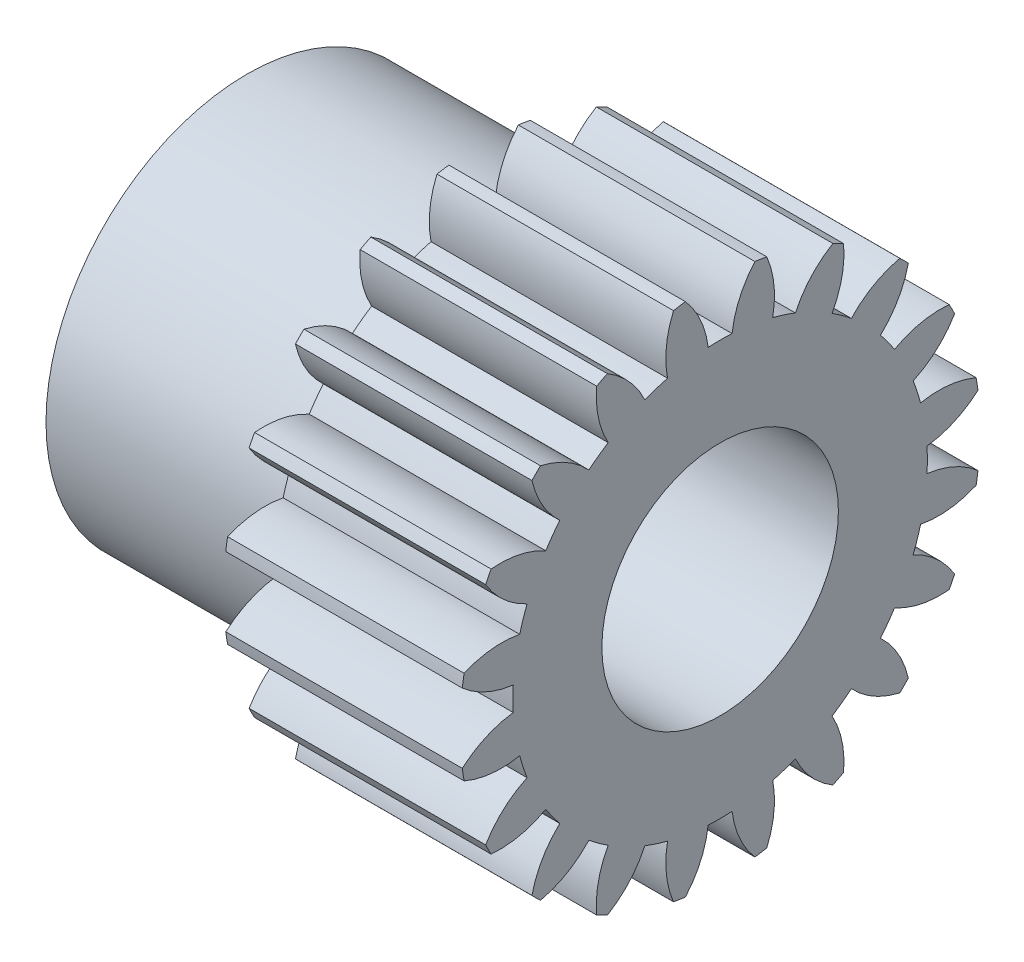
SolidWorks part; units mm, degrees
material "Plain Carbon Steel"
ref_plane "Plane1" through (0, 0, 0) normal (0, 0, 1) x (1, 0, 0)
ref_plane "Plane2" through (0, 0, 0) normal (0, 1, 0) x (1, 0, 0)
ref_plane "Plane3" through (0, 0, 0) normal (1, 0, 0) x (0, 0, -1)
sketch "HoldingSke" plane through (0, 0, 0) normal (0, 1, 0) x (1, 0, 0)
  line L0 (0, 0) -> (477.3639, -173.7462)
  line L1 (-15, 0) -> (100, 0) construction
  line L2 (0, 0) -> (-2.1039, 2.3779)
  line L3 (0, 0) -> (-11.863, 4.5341)
  line L4 (0, 0) -> (8.1152, 2.9537)
  line L5 (0, 0) -> (-23.7986, -8.8762)
  line L6 (0, 0) -> (-10.5278, -7.1032)
  line L7 (-2.1039, 2.3779) -> (3.3635, 27.1825)
  line L8 (-76.2, 54.61) -> (-61.976, 54.61)
  line L9 (-71.009, 38.7566) -> (-53.1078, 45.2721)
  line L10 (-76.2, 71.12) -> (104.1128, 71.12)
  line L11 (0, 0) -> (-12.7, 0)
  line L12 (-76.2, 101.6) -> (-76.1492, 101.6)
  line L13 (24.9733, 27.94) -> (52.9518, 28.4284)
  line L14 (24.9733, 27.94) -> (25.0241, 27.9398)
  line L15 (24.9733, 27.94) -> (100.4021, 29.52)
  circle A0 centre (0, 0) radius 6.35
  circle A1 centre (0, 0) radius 10.795
  circle A2 centre (0, 0) radius 10.795
  circle A3 centre (0, 0) radius 6.35
  dimension "MHD" = 21.59
  dimension "Hub_dia" = 21.59
  dimension "Bore" = 12.7
  dimension "MBD" = 12.7
  dimension "Num_teeth" = 20
  dimension "Pitch_radius" = 180.3128
  dimension "Pitch" = 508
  dimension "Width" = 12.7
  dimension "Overall_len" = 25.4
  dimension "Show_teeth" = 20
  dimension "Thickness" = 12.7
  dimension "OAL" = 25.4001
  dimension "T_dim" = 14.224
  dimension "Ap" = 20
  dimension "H" = 19.05
  dimension "Backlash" = 0.0508
  dimension "Addendum_fac" = 1
  dimension "Dedendum_fac" = 1.2
  dimension "Clearance_fac" = 0.2
  dimension "Dedendum_add" = 0.0508
sketch "BasProSke" plane through (0, 0, 0) normal (0, 1, 0) x (1, 0, 0)
  line L0 (-10, 0) -> (60, 0) construction
  line L1 (0, 0) -> (0, 13.97)
  line L2 (0, 0) -> (12.7, 0)
  line L3 (12.7, 0) -> (12.7, 13.97)
  line L4 (12.7, 13.97) -> (0, 13.97)
  dimension "Diameter" = 27.94
  dimension "Thickness" = 12.7
revolve "Base-Revolve" add sketch "BasProSke" angle 360 about L0
sketch "TooCutSke" plane through (0, 0, 0) normal (1, 0, 0) x (0, 0, -1)
  line L1 (0, 0) -> (0, 107) construction
  line L2 (0, 0) -> (-1.0853, 12.6535) construction
  line L3 (0, 0) -> (-3.9633, 25.0231) construction
  line L4 (-1.0853, 12.6535) -> (-1.9816, 12.5116) construction
  arc A0 (0.6405, 11.1067) -> (-0.6405, 11.1067) centre (0, 0) ccw
  arc A1 (1.8856, 13.8678) -> (-1.8856, 13.8678) centre (0, 0) ccw
  circle A2 centre (0, 0) radius 12.7 construction
  circle A3 centre (0, 0) radius 11.9341 construction
  arc A4 (-0.6405, 11.1067) -> (-1.8856, 13.8678) centre (-5.6834, 10.4939) ccw
  arc A5 (1.8856, 13.8678) -> (0.6405, 11.1067) centre (5.6834, 10.4939) ccw
  dimension "Root_dia" = 22.2504
  dimension "Overcut_dia" = 27.9908
  dimension "Pitch_dia" = 25.4
  dimension "Base_dia" = 23.8682
  dimension "Flank_rad" = 5.08
  dimension "Half_ang" = 9
  dimension "Half_CT" = 0.9075
extrude "ToothCut" cut sketch "TooCutSke" along normal through all
fillet "Breaks" [suppressed] radius 0.0254
fillet "RootFillets" [suppressed] radius 0.3048
pattern_circular "TeethCuts" count 20 every 18 about axis through (-10, 0, 0) along (1, 0, 0) of "ToothCut", "RootFillets", "Breaks"
sketch "HubNeaOneSke" plane through (0, 0, 0) normal (-1, 0, 0) x (0, 0, 1)
  circle A0 centre (0, 0) radius 10.795
  dimension "Diameter" = 21.59
extrude "HubNearOne" add sketch "HubNeaOneSke" along normal blind 12.7001
sketch "HubNeaBotSke" plane through (0, 0, 0) normal (-1, 0, 0) x (0, 0, 1)
  circle A0 centre (0, 0) radius 10.795
  dimension "Diameter" = 21.59
extrude "HubNearBoth" [suppressed] add sketch "HubNeaBotSke" along normal blind 6.35
ref_plane "FarPln" through (12.7, 0, 0) normal (1, 0, 0) x (0, 0, -1)
sketch "HubFarSke" plane through (12.7, 0, 0) normal (1, 0, 0) x (0, 0, -1)
  circle A0 centre (0, 0) radius 10.795
  dimension "Diameter" = 21.59
extrude "HubFar" [suppressed] add sketch "HubFarSke" along normal blind 6.35
sketch "BorSke" plane through (0, 0, 0) normal (1, 0, 0) x (0, 0, -1)
  circle A0 centre (0, 0) radius 6.35
  dimension "Diameter" = 12.7
extrude "Bore" cut sketch "BorSke" along normal mid plane 50.8001
sketch "KeySke" plane through (0, 0, 0) normal (1, 0, 0) x (0, 0, -1)
  line L0 (-1.5875, 0) -> (-1.5875, 7.874)
  line L1 (-1.5875, 7.874) -> (1.5875, 7.874)
  line L2 (1.5875, 7.874) -> (1.5875, 0)
  line L3 (0, 0) -> (0, 34) construction
  line L4 (-1.5875, 0) -> (1.5875, 0)
  dimension "Offset" = 7.874
  dimension "Width" = 3.175
extrude "Keyway" [suppressed] cut sketch "KeySke" along normal mid plane 50.8001
pattern_circular "Keyway2" [suppressed] count 2 every 90 about axis through (-10, 0, 0) along (1, 0, 0)
equation "' \"Pitch@HoldingSke\" = 4"
equation "' \"Num_teeth@HoldingSke\" = 12"
equation "' \"Ap@HoldingSke\" =  20"
equation "' \"Width@HoldingSke\" = 0.5"
equation "' \"Hub_dia@HoldingSke\"= 1"
equation "' \"Overall_len@HoldingSke\" = 1.0"
equation "' \"Bore@HoldingSke\" = 0.75"
equation "' \"T_dim@HoldingSke\" = 0.85"
equation "' \"Width@KeySke\" = 0.25"
equation "' \"Show_teeth@HoldingSke\" = 13"
equation "' \"Backlash@HoldingSke\" = 0.009"
equation "' \"Addendum_fac@HoldingSke\" = 1.0"
equation "' \"Dedendum_fac@HoldingSke\" = 1.25"
equation "' \"Dedendum_add@HoldingSke\" = 0.00005"
equation "' \"Clearance_fac@HoldingSke\" = 0.25"
equation "' \"Pitch@HoldingSke\" = 0.5"
equation "' \"Num_teeth@HoldingSke\" = 23"
equation "' \"Show_teeth@HoldingSke\" = 23"
equation "' \"Backlash@HoldingSke\" = 0.0375"
equation "\"Overcut_dia@TooCutSke\" = (\"Num_teeth@HoldingSke\" + 2 * \"Addendum_fac@HoldingSke\") / \"Pitch@HoldingSke\" + 0.002"
equation "\"Pitch_dia@TooCutSke\" = \"Num_teeth@HoldingSke\" / \"Pitch@HoldingSke\""
equation "\"Base_dia@TooCutSke\" = \"Num_teeth@HoldingSke\" / \"Pitch@HoldingSke\" * cos((\"Ap@HoldingSke\"  * 3.14159265 / 180))"
equation "\"Root_dia@TooCutSke\" = (\"Num_teeth@HoldingSke\" + 2) / \"Pitch@HoldingSke\" - 2 * (\"Addendum_fac@HoldingSke\" + \"Dedendum_fac@HoldingSke\") / \"Pitch@HoldingSke\" - \"Dedendum_add@HoldingSke\" * 2"
equation "\"Half_ang@TooCutSke\" = 180 / \"Num_teeth@HoldingSke\""
equation "\"Half_CT@TooCutSke\" = \"Num_teeth@HoldingSke\" / \"Pitch@HoldingSke\" * sin((3.14159265 / 2 / \"Num_teeth@HoldingSke\")) / 2 - 7 * \"Backlash@HoldingSke\" / 4"
equation "\"Flank_rad@TooCutSke\" = \"Num_teeth@HoldingSke\" / \"Pitch@HoldingSke\" / 5"
equation "\"Radius@RootFillets\" = \"Clearance_fac@HoldingSke\" / \"Pitch@HoldingSke\" + \"Dedendum_add@HoldingSke\""
equation "\"Break_rad@Breaks\" = 0.02 / \"Pitch@HoldingSke\""
equation "\"Thickness@HoldingSke\" = \"Width@HoldingSke\""
equation "\"OAL@HoldingSke\" = \"Thickness@HoldingSke\""
equation "\"MHD@HoldingSke\" = (\"Num_teeth@HoldingSke\" + 2) / \"Pitch@HoldingSke\" - 2 * (\"Addendum_fac@HoldingSke\" + \"Dedendum_fac@HoldingSke\")  / \"Pitch@HoldingSke\" - \"Dedendum_add@HoldingSke\" * 2"
equation "\"MBD@HoldingSke\" = (\"Num_teeth@HoldingSke\" + 2) / \"Pitch@HoldingSke\" - 2 * (\"Addendum_fac@HoldingSke\" + \"Dedendum_fac@HoldingSke\")  / \"Pitch@HoldingSke\" - \"Dedendum_add@HoldingSke\" * 2 - 0.002"
equation "\"MHD@HoldingSke\" = ((sgn( \"MHD@HoldingSke\" - \"Hub_dia@HoldingSke\" )-1)*( \"MHD@HoldingSke\" - \"Hub_dia@HoldingSke\" ))/-2+ \"Hub_dia@HoldingSke\""
equation "\"MBD@HoldingSke\" = ((sgn( \"MBD@HoldingSke\" - \"Bore@HoldingSke\" )-1)*( \"MBD@HoldingSke\" - \"Bore@HoldingSke\" ))/-2+ \"Bore@HoldingSke\""
equation "\"OAL@HoldingSke\" = ((sgn( \"OAL@HoldingSke\" - \"Overall_len@HoldingSke\" )+1)*( \"OAL@HoldingSke\" - \"Overall_len@HoldingSke\" ))/2 + \"Overall_len@HoldingSke\" + 0.000002"
equation "\"Num_teeth@TeethCuts\" = int( \"Show_teeth@HoldingSke\" ) + 1"
equation "\"Num_teeth@TeethCuts\" = ((sgn( \"Num_teeth@TeethCuts\" - \"Num_teeth@HoldingSke\" )-1)*( \"Num_teeth@TeethCuts\" - \"Num_teeth@HoldingSke\" ))/-2+ \"Num_teeth@HoldingSke\""
equation "\"Num_teeth@TeethCuts\" = ((sgn( \"Num_teeth@TeethCuts\" - 2.0)+1)*( \"Num_teeth@TeethCuts\" - 2.0))/2 +2.0"
equation "\"Angle@TeethCuts\" = 360.0 / \"Num_teeth@HoldingSke\""
equation "\"Diameter@BasProSke\" = (\"Num_teeth@HoldingSke\" + 2 * \"Addendum_fac@HoldingSke\") / \"Pitch@HoldingSke\""
equation "\"Thickness@BasProSke\"  = \"Thickness@HoldingSke\""
equation "' \"Fillet_rad@BasProSke\" =  \"Thickness@HoldingSke\" * 0.05"
equation "\"MHD@HoldingSke\" = ((sgn( \"MHD@HoldingSke\" - \"Root_dia@TooCutSke\" )-1)*( \"MHD@HoldingSke\" - \"Root_dia@TooCutSke\" ))/-2+ \"Root_dia@TooCutSke\""
equation "\"Diameter@HubNeaOneSke\" = \"MHD@HoldingSke\""
equation "\"Length@HubNearOne\" = \"OAL@HoldingSke\" - \"Thickness@BasProSke\""
equation "\"Diameter@HubNeaBotSke\" = \"MHD@HoldingSke\""
equation "\"Length@HubNearBoth\" = ( \"OAL@HoldingSke\" - \"Thickness@BasProSke\" ) / 2.0"
equation "\"Thickness@FarPln\" = \"Thickness@BasProSke\""
equation "\"Diameter@HubFarSke\" = \"MHD@HoldingSke\""
equation "\"Length@HubFar\" = ( \"OAL@HoldingSke\" - \"Thickness@BasProSke\" ) / 2.0"
equation "\"Diameter@BorSke\" = \"MBD@HoldingSke\""
equation "\"D1@Bore\" = \"OAL@HoldingSke\" * 2.0"
equation "\"D1@Keyway\" = \"OAL@HoldingSke\" * 2.0"
equation "\"Offset@KeySke\" = \"T_dim@HoldingSke\" - \"MBD@HoldingSke\" / 2.0"
